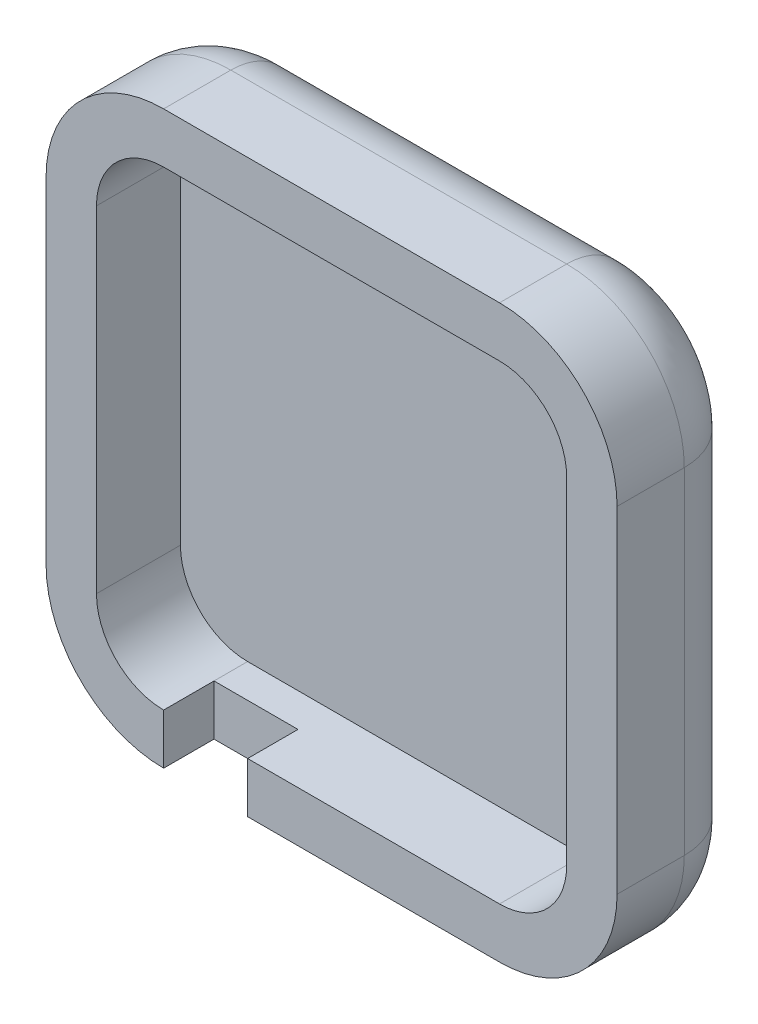
SolidWorks part; units mm, degrees
ref_plane "Front Plane" through (0, 0, 0) normal (0, 0, 1) x (1, 0, 0)
ref_plane "Top Plane" through (0, 0, 0) normal (0, 1, 0) x (1, 0, 0)
ref_plane "Right Plane" through (0, 0, 0) normal (1, 0, 0) x (0, 0, -1)
sketch "Sketch1" plane through (0, 0, 0) normal (0, 0, 1) x (1, 0, 0)
  line L1 (0, 0) -> (17, 0)
  line L2 (0, 0) -> (0, 17)
  line L3 (0, 17) -> (17, 17)
  line L4 (17, 0) -> (17, 17)
  dimension "D1" = 17
  dimension "D2" = 17
extrude "Boss-Extrude1" add sketch "Sketch1" along normal blind 4
sketch "Sketch2" plane through (0, 0, 4) normal (0, 0, 1) x (1, 0, 0)
  line L0 (17, 17) -> (0, 17) construction
  line L1 (1.5, 15.5) -> (15.5, 15.5)
  line L2 (1.5, 15.5) -> (1.5, 1.5)
  line L3 (1.5, 1.5) -> (15.5, 1.5)
  line L4 (15.5, 15.5) -> (15.5, 1.5)
  line L5 (0, 0) -> (17, 0) construction
  line L6 (17, 0) -> (17, 17) construction
  line L7 (0, 17) -> (0, 0) construction
  dimension "D1" = 1.5
  dimension "D2" = 1.5
  dimension "D3" = 1.5
  dimension "D4" = 1.5
extrude "Cut-Extrude1" cut sketch "Sketch2" against normal blind 2.5
fillet "Fillet1" radius 2 4 edges at (15.5, 1.5, 2.75) (1.5, 15.5, 2.75) (1.5, 1.5, 2.75) (15.5, 15.5, 2.75)
fillet "Fillet2" radius 3.5 4 edges at (17, 0, 2) (0, 0, 2) (17, 17, 2) (0, 17, 2)
sketch "Sketch3" plane through (0, 0, 4) normal (0, 0, 1) x (1, 0, 0)
  line L0 (3.5, 0) -> (13.5, 0) construction
  line L1 (3.5, 1.5) -> (6, 1.5)
  line L2 (3.5, 1.5) -> (3.5, 0)
  line L3 (3.5, 0) -> (6, 0)
  line L4 (6, 1.5) -> (6, 0)
  dimension "D1" = 2.5
extrude "Cut-Extrude2" cut sketch "Sketch3" against normal blind 1.5
fillet "Fillet3" radius 2 8 edges at (15.9749, 1.0251, 0) (8.5, 0, 0) (1.0251, 1.0251, 0) (0, 8.5, 0) (1.0251, 15.9749, 0) (8.5, 17, 0) (15.9749, 15.9749, 0) (17, 8.5, 0)
